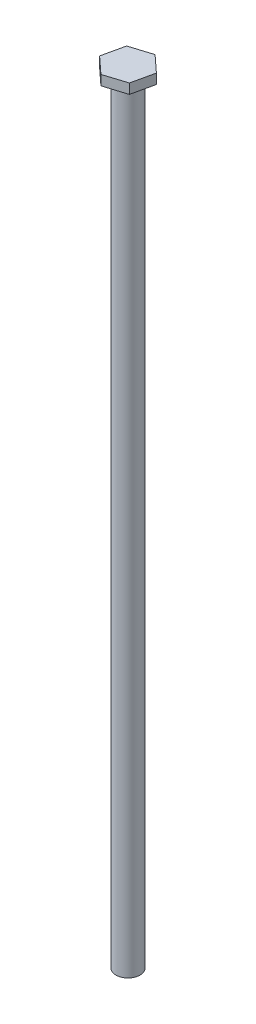
SolidWorks part; units mm, degrees
ref_plane "Front Plane" through (0, 0, 0) normal (0, 0, 1) x (1, 0, 0)
ref_plane "Top Plane" through (0, 0, 0) normal (0, 1, 0) x (1, 0, 0)
ref_plane "Right Plane" through (0, 0, 0) normal (1, 0, 0) x (0, 0, -1)
sketch "Sketch2" plane through (0, 0, 0) normal (0, 1, 0) x (1, 0, 0)
  circle A0 centre (0, 0) radius 0.6114
extrude "Boss-Extrude3" add sketch "Sketch2" along normal blind 4 and the other way blind 50
sketch "Sketch3" plane through (0, 4, 0) normal (0, 1, 0) x (1, 0, 0)
  line L1 (0.8425, -0.7742) -> (1.0917, 0.3425)
  line L2 (1.0917, 0.3425) -> (0.2492, 1.1167)
  line L3 (0.2492, 1.1167) -> (-0.8425, 0.7742)
  line L4 (-0.8425, 0.7742) -> (-1.0917, -0.3425)
  line L5 (-1.0917, -0.3425) -> (-0.2492, -1.1167)
  line L6 (-0.2492, -1.1167) -> (0.8425, -0.7742)
  circle A0 centre (0, 0) radius 0.9909 construction
  point P1 (0, 0)
extrude "Boss-Extrude4" add sketch "Sketch3" along normal blind 0.5
sketch "Sketch4" plane through (0, -50, 0) normal (0, -1, 0) x (-1, 0, 0)
  line L1 (1.1366, 1.7225) -> (-2.8642, 1.7225)
  line L2 (1.1366, 1.7225) -> (1.1366, -1.911)
  line L3 (1.1366, -1.911) -> (-2.8642, -1.911)
  line L4 (-2.8642, 1.7225) -> (-2.8642, -1.911)
extrude "Cut-Extrude1" cut sketch "Sketch4" against normal blind 15
